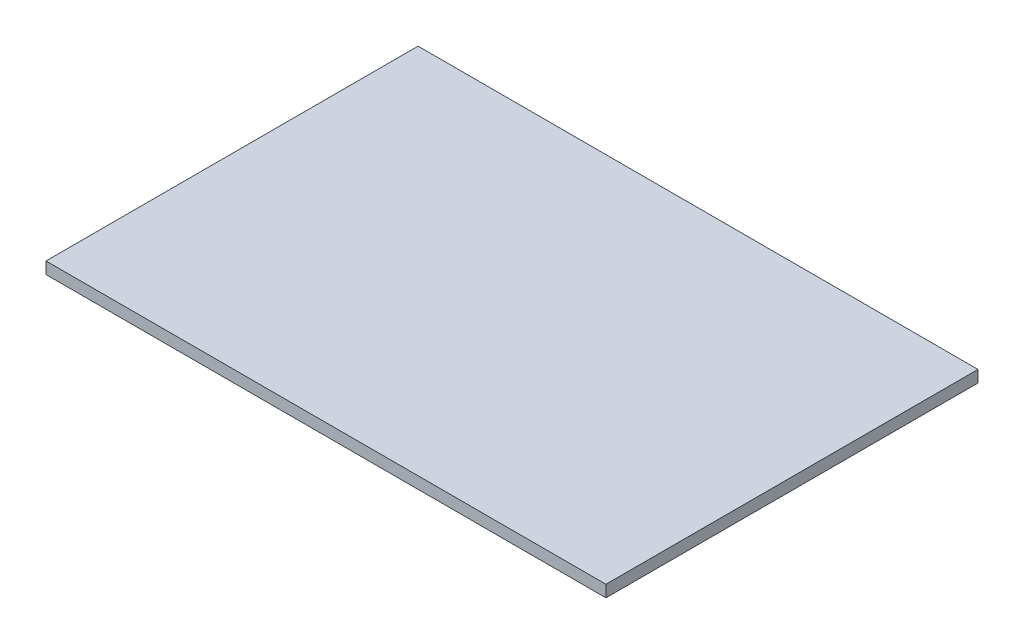
SolidWorks part; units mm, degrees
ref_plane "Front Plane" through (0, 0, 0) normal (0, 0, 1) x (1, 0, 0)
ref_plane "Top Plane" through (0, 0, 0) normal (0, 1, 0) x (1, 0, 0)
ref_plane "Right Plane" through (0, 0, 0) normal (1, 0, 0) x (0, 0, -1)
sketch "Sketch5" plane through (0, 0, 0) normal (0, 1, 0) x (1, 0, 0)
  line L1 (-38, -25.25) -> (38, -25.25)
  line L2 (-38, -25.25) -> (-38, 25.25)
  line L3 (-38, 25.25) -> (38, 25.25)
  line L4 (38, -25.25) -> (38, 25.25)
  line L5 (-38, -25.25) -> (38, 25.25) construction
  line L6 (-38, 25.25) -> (38, -25.25) construction
  point P0 (0, 0)
  dimension "D1" = 76
  dimension "D2" = 50.5
extrude "Boss-Extrude1" add sketch "Sketch5" along normal blind 1.6
